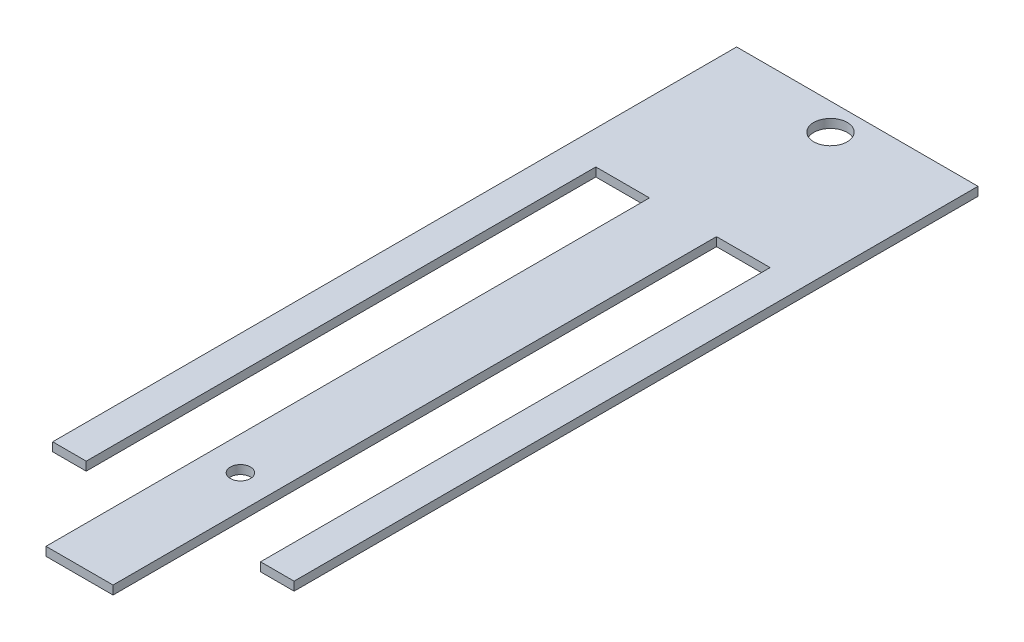
SolidWorks part; units mm, degrees
ref_plane "前视基准面" through (0, 0, 0) normal (0, 0, 1) x (1, 0, 0)
ref_plane "上视基准面" through (0, 0, 0) normal (0, 1, 0) x (1, 0, 0)
ref_plane "右视基准面" through (0, 0, 0) normal (1, 0, 0) x (0, 0, -1)
sketch "草图1" plane through (0, 0, 0) normal (0, 1, 0) x (1, 0, 0)
  line L0 (-2.5, 29) -> (-9, 29)
  line L1 (-2.5, 29) -> (2.5, 29)
  line L2 (-2.5, 29) -> (-2.5, -29)
  line L3 (-2.5, -29) -> (2.5, -29)
  line L4 (2.5, 29) -> (2.5, -29)
  line L5 (-2.5, 29) -> (2.5, -29) construction
  line L6 (-2.5, -29) -> (2.5, 29) construction
  line L7 (-9, 29) -> (-9, -22)
  line L8 (-9, -22) -> (-6.5, -22)
  line L9 (-6.5, -22) -> (-6.5, 16)
  line L10 (-6.5, 16) -> (-2.5, 16)
  line L11 (6.5, -22) -> (9, -22)
  line L12 (9, -22) -> (9, 29)
  line L13 (9, 29) -> (2.5, 29)
  line L14 (2.5, 16) -> (6.5, 16)
  line L15 (6.5, 16) -> (6.5, -22)
  point P0 (0, 0)
  point P16 (-5.75, 29)
  dimension "D1" = 2.5
  dimension "D2" = 2.5
  dimension "D3" = 5
  dimension "D4" = 58
  dimension "D5" = 51
  dimension "D6" = 18
  dimension "D7" = 13
extrude "凸台-拉伸1" add sketch "草图1" along normal blind 0.65 contours L9 L10 L2 L0 L7 L8 | L4 L1 L2 L3 | L14 L15 L11 L12 L13 L4
sketch "草图2" plane through (0, 0.65, 0) normal (0, 1, 0) x (1, 0, 0)
  line L0 (9, 29) -> (-9, 29) construction
  line L1 (9, -22) -> (9, 29) construction
  circle A0 centre (0, 27) radius 1.25
  dimension "D1" = 2.5
  dimension "D2" = 2
  dimension "D3" = 9
extrude "切除-拉伸1" cut sketch "草图2" against normal blind 10
sketch "草图3" plane through (0, 0, 0) normal (0, -1, 0) x (1, 0, 0)
  line L0 (-2.5, 29) -> (2.5, 29) construction
  circle A0 centre (0, 17) radius 0.75
  dimension "D1" = 1.5
  dimension "D2" = 12
extrude "切除-拉伸2" cut sketch "草图3" against normal blind 10
